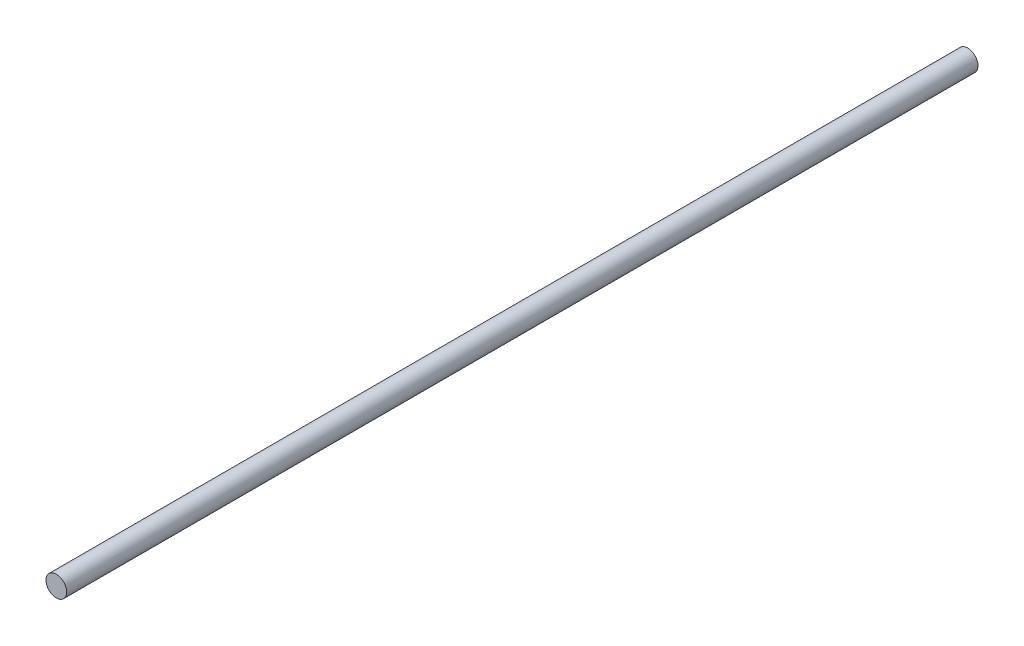
SolidWorks part; units mm, degrees
ref_plane "Front Plane" through (0, 0, 0) normal (0, 0, 1) x (1, 0, 0)
ref_plane "Top Plane" through (0, 0, 0) normal (0, 1, 0) x (1, 0, 0)
ref_plane "Right Plane" through (0, 0, 0) normal (1, 0, 0) x (0, 0, -1)
sketch "Sketch1" plane through (0, 0, 0) normal (0, 0, 1) x (1, 0, 0)
  circle A0 centre (0, 0) radius 3.175
  dimension "D1" = 6.35
extrude "Boss-Extrude1" add sketch "Sketch1" along normal blind 280.5354 contours A0
equation "\"Dia\" = .250in"
equation "\"A\"= pi * \"Dia\" ^ 2 / 4"
equation "\"DF\" = .009in"
equation "\"E\"= 10007604"
equation "\"F\"= 400"
equation "\"L\" =  ( \"DF\" * \"A\" * \"E\" )  / \"F\""
